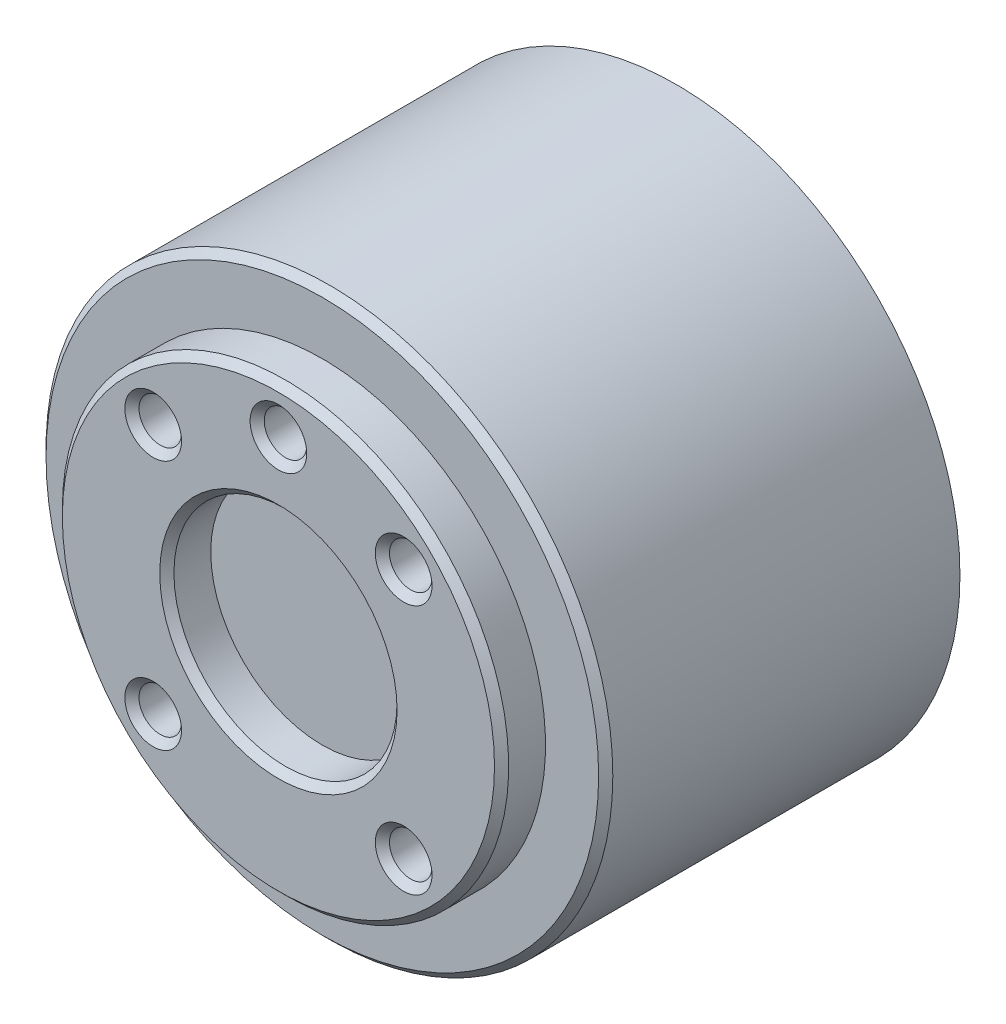
SolidWorks part; units mm, degrees
ref_plane "Ebene vorne" through (0, 0, 0) normal (0, 0, 1) x (1, 0, 0)
ref_plane "Ebene oben" through (0, 0, 0) normal (0, 1, 0) x (1, 0, 0)
ref_plane "Ebene rechts" through (0, 0, 0) normal (1, 0, 0) x (0, 0, -1)
sketch "Skizze1" plane through (0, 0, 0) normal (0, 0, 1) x (1, 0, 0)
  circle A0 centre (0, 0) radius 40
  dimension "D1" = 80
extrude "Aufsatz-Linear austragen1" add sketch "Skizze1" along normal blind 50
sketch "Skizze2" plane through (0, 0, 50) normal (0, 0, 1) x (1, 0, 0)
  circle A0 centre (0, 0) radius 31.5
  circle A1 centre (0, 0) radius 15.75
  circle A2 centre (0, 25) radius 3
  circle A3 centre (17.6777, 17.6777) radius 3
  circle A4 centre (17.6777, -17.6777) radius 3
  circle A5 centre (-17.6777, -17.6777) radius 3
  circle A6 centre (-17.6777, 17.6777) radius 3
  point P10 (0, 0)
  point P18 (0, 0)
  dimension "D1" = 63
  dimension "D2" = 31.5
  dimension "D4" = 6
  dimension "D3" = 25
  dimension "D5" = 2
  dimension "D6" = 4
extrude "Aufsatz-Linear austragen2" add sketch "Skizze2" along normal blind 6.2
chamfer "Fase1" distance 1 angle 45 8 edges at (-14.6777, -17.6777, 56.2) (15.75, 0, 56.2) (20.6777, -17.6777, 56.2) (20.6777, 17.6777, 56.2) (3, 25, 56.2) (-14.6777, 17.6777, 56.2) (40, 0, 50) (31.5, 0, 56.2)
